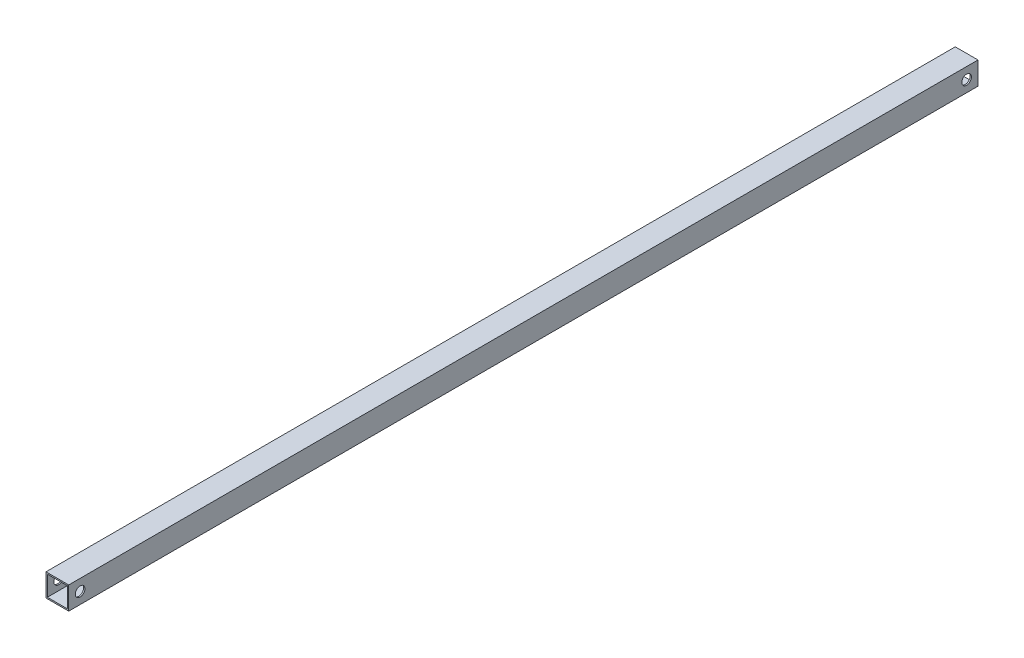
SolidWorks part; units mm, degrees
ref_plane "Front Plane" through (0, 0, 0) normal (0, 0, 1) x (1, 0, 0)
ref_plane "Top Plane" through (0, 0, 0) normal (0, 1, 0) x (1, 0, 0)
ref_plane "Right Plane" through (0, 0, 0) normal (1, 0, 0) x (0, 0, -1)
sketch "Sketch1" plane through (0, 0, 0) normal (0, 0, 1) x (1, 0, 0)
  line L0 (-8.8, -8.8) -> (-8.8, 8.8)
  line L1 (10, -10) -> (-10, -10)
  line L2 (10, -10) -> (10, 10)
  line L3 (10, 10) -> (-10, 10)
  line L4 (-10, -10) -> (-10, 10)
  line L5 (10, -10) -> (-10, 10) construction
  line L6 (10, 10) -> (-10, -10) construction
  line L7 (8.8, 8.8) -> (-8.8, 8.8)
  line L8 (8.8, -8.8) -> (8.8, 8.8)
  line L9 (8.8, -8.8) -> (-8.8, -8.8)
  point P0 (0, 0)
  dimension "D1" = 20
  dimension "D2" = 1.2
extrude "Boss-Extrude1" add sketch "Sketch1" along normal blind 800
sketch "Sketch2" plane through (10, 0, 0) normal (1, 0, 0) x (0, 0, -1)
  line L0 (0, -10) -> (0, 10) construction
  line L1 (0, 0) -> (-800, 0) construction
  line L2 (-800, -10) -> (-800, 10) construction
  circle A0 centre (-10, 0) radius 4.25
  circle A1 centre (-790, 0) radius 4.25
  point P11 (0, 0)
  point P12 (0, 0)
  dimension "D1" = 8.5
  dimension "D2" = 10
  dimension "D3" = 10
extrude "Cut-Extrude1" cut sketch "Sketch2" against normal through all
